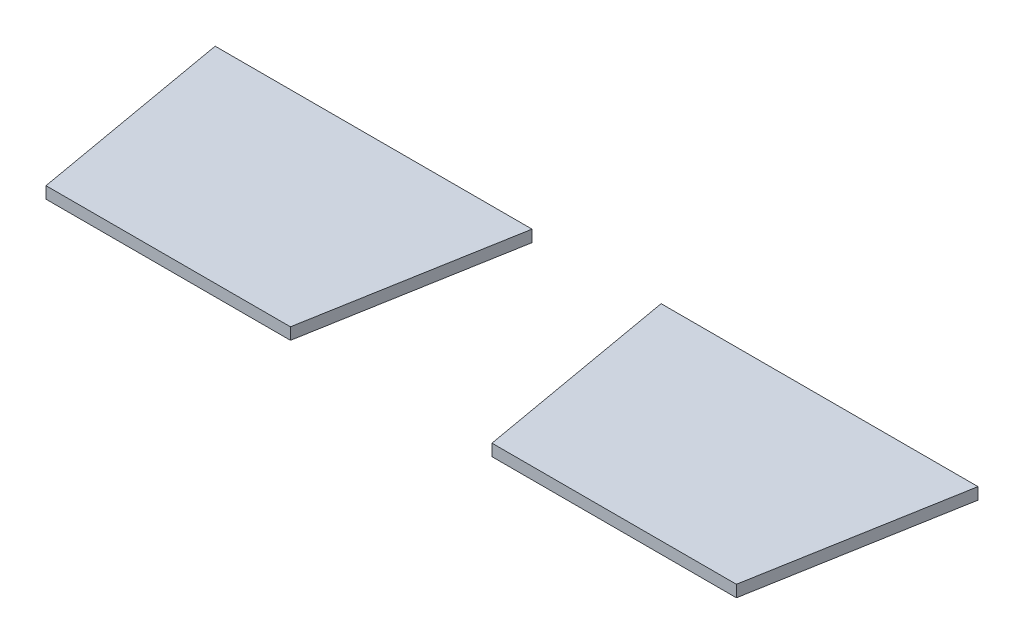
SolidWorks part; units mm, degrees
ref_plane "Front" through (0, 0, 0) normal (0, 0, 1) x (1, 0, 0)
ref_plane "Top" through (0, 0, 0) normal (0, 1, 0) x (1, 0, 0)
ref_plane "Right" through (0, 0, 0) normal (1, 0, 0) x (0, 0, -1)
sketch "草图1" plane through (0, 0, 0) normal (0, 1, 0) x (1, 0, 0)
  line L0 (-65, 17.5) -> (-58.8286, -17.5)
  line L1 (-65, 17.5) -> (-11, 17.5) construction
  line L2 (-65, 17.5) -> (-65, -17.5) construction
  line L3 (-65, -17.5) -> (65, -17.5) construction
  line L4 (65, 17.5) -> (65, -17.5) construction
  line L5 (-65, 17.5) -> (65, -17.5) construction
  line L6 (-65, -17.5) -> (65, 17.5) construction
  line L7 (58.8286, -17.5) -> (17.1714, -17.5)
  line L8 (-11, 17.5) -> (-17.1714, -17.5)
  line L9 (-58.8286, -17.5) -> (-17.1714, -17.5)
  line L10 (-65, 17.5) -> (-11, 17.5)
  line L11 (0, 17.5) -> (0, -17.5) construction
  line L12 (0, 17.5) -> (65, 17.5) construction
  line L13 (65, 17.5) -> (58.8286, -17.5)
  line L14 (65, 17.5) -> (11, 17.5)
  line L15 (11, 17.5) -> (17.1714, -17.5)
  point P0 (0, 0)
  dimension "D1" = 130
  dimension "D2" = 35
  dimension "D3" = 10
  dimension "D4" = 11
extrude "凸台-拉伸1" add sketch "草图1" along normal blind 2
